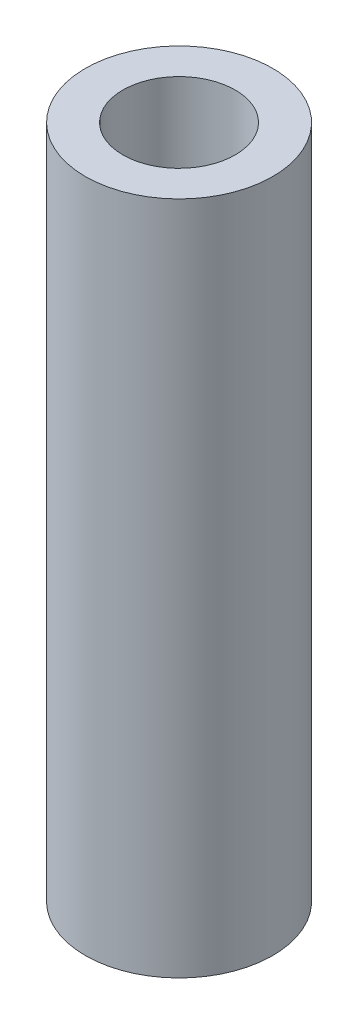
SolidWorks part; units mm, degrees
material "1060 合金"
ref_plane "前视基准面" through (0, 0, 0) normal (0, 0, 1) x (1, 0, 0)
ref_plane "上视基准面" through (0, 0, 0) normal (0, 1, 0) x (1, 0, 0)
ref_plane "右视基准面" through (0, 0, 0) normal (1, 0, 0) x (0, 0, -1)
other "Configuration Table"
sketch "草图1" plane through (0, 0, 0) normal (0, 1, 0) x (1, 0, 0)
  circle A0 centre (0, 0) radius 2.5
  circle A1 centre (0, 0) radius 1.5
  dimension "D1" = 3
  dimension "5" = 5
extrude "凸台-拉伸1" add sketch "草图1" along normal blind 18
